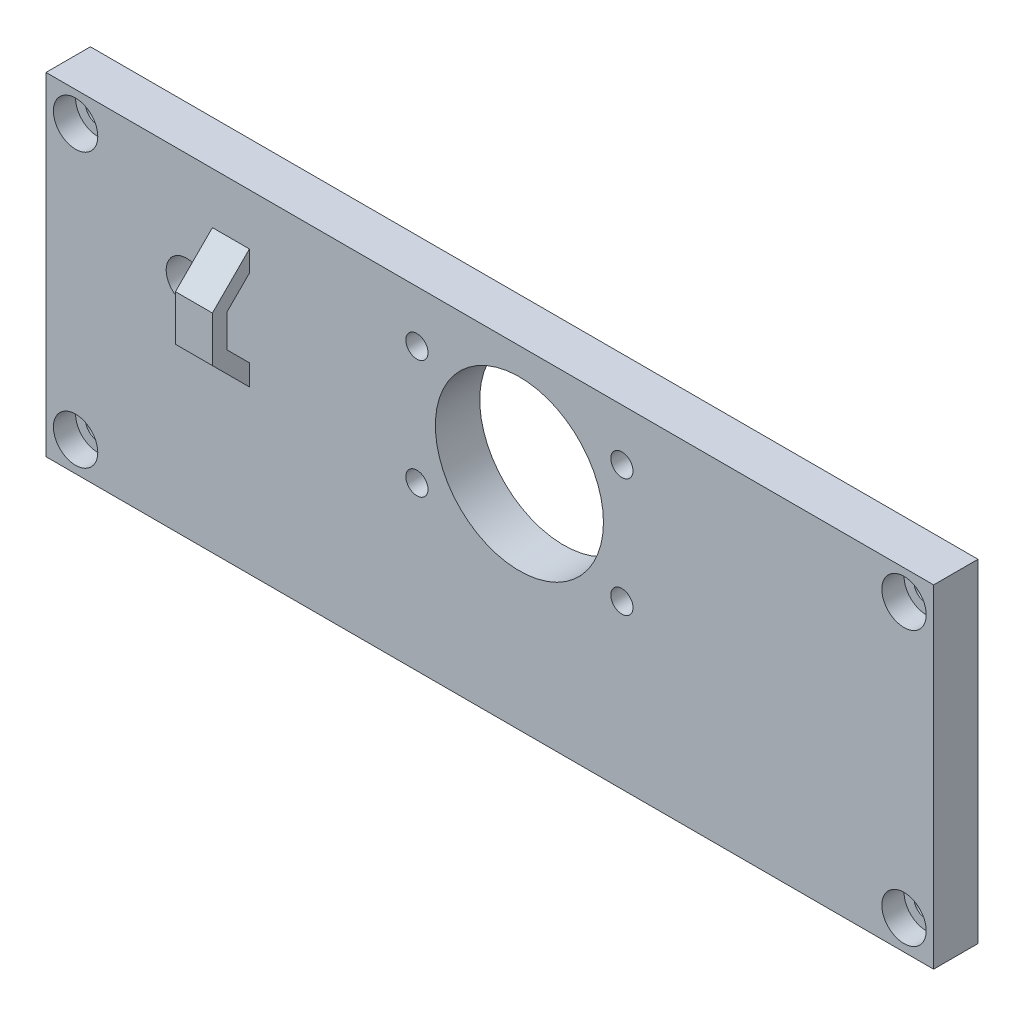
SolidWorks part; units mm, degrees
ref_plane "Front Plane" through (0, 0, 0) normal (0, 0, 1) x (1, 0, 0)
ref_plane "Top Plane" through (0, 0, 0) normal (0, 1, 0) x (1, 0, 0)
ref_plane "Right Plane" through (0, 0, 0) normal (1, 0, 0) x (0, 0, -1)
sketch "Sketch1" plane through (0, 0, 0) normal (0, 0, 1) x (1, 0, 0)
  line L0 (60, 45) -> (60, 0) construction
  line L1 (0, 0) -> (120, 0)
  line L2 (0, 0) -> (0, 45)
  line L3 (0, 45) -> (120, 45)
  line L4 (120, 0) -> (120, 45)
  line L5 (0, 22.5) -> (120, 22.5) construction
  line L6 (50.1436, 38) -> (64, 30) construction
  line L7 (64, 30) -> (42.232, 30) construction
  line L8 (64, 30) -> (64, 38.4979) construction
  circle A0 centre (64, 30) radius 11.3625
  circle A1 centre (4, 41) radius 1.65
  circle A2 centre (4, 4) radius 1.65
  circle A3 centre (116, 41) radius 1.65
  circle A4 centre (116, 4) radius 1.65
  circle A5 centre (50.1436, 38) radius 1.5
  circle A6 centre (50.1436, 22) radius 1.5
  circle A9 centre (77.8564, 22) radius 1.5
  circle A10 centre (77.8564, 38) radius 1.5
  dimension "D3" = 22.725
  dimension "D4" = 4
  dimension "D5" = 3.3
  dimension "D6" = 4
  dimension "D7" = 15
  dimension "D10" = 3
  dimension "D1" = 45
  dimension "D2" = 120
  dimension "D8" = 16
  dimension "D9" = 60
  dimension "D11" = 4
extrude "Boss-Extrude1" add sketch "Sketch1" along normal blind 6
sketch "Sketch2" plane through (0, 0, 6) normal (0, 0, 1) x (1, 0, 0)
  circle A0 centre (116, 4) radius 1.65 construction
  circle A1 centre (116, 41) radius 1.65 construction
  circle A2 centre (4, 4) radius 1.65 construction
  circle A3 centre (4, 41) radius 1.65 construction
  circle A4 centre (116, 4) radius 1.65
  circle A5 centre (116, 41) radius 1.65
  circle A6 centre (4, 4) radius 1.65
  circle A7 centre (4, 41) radius 1.65
  circle A8 centre (4, 41) radius 3
  circle A9 centre (4, 4) radius 3
  circle A10 centre (116, 4) radius 3
  circle A11 centre (116, 41) radius 3
  dimension "D1" = 1.35
extrude "Cut-Extrude1" cut sketch "Sketch2" against normal blind 3
sketch "Sketch3" plane through (0, 0, 6) normal (0, 0, 1) x (1, 0, 0)
  circle A0 centre (19, 30) radius 2.75
  circle A1 centre (64, 30) radius 11.3625 construction
  dimension "D1" = 5.5
  dimension "D2" = 0
  dimension "D3" = 45
extrude "Cut-Extrude2" cut sketch "Sketch3" against normal through all
sketch "Sketch4" plane through (0, 0, 0) normal (-1, 0, 0) x (0, 0, 1)
  line L0 (6, 35.25) -> (9, 32.25)
  line L1 (6, 45) -> (6, 0) construction
  line L2 (9, 32.25) -> (9, 27.75)
  line L3 (9, 27.75) -> (6, 24.75)
  line L4 (6, 45) -> (0, 45) construction
  line L5 (7.4142, 36.6642) -> (11, 33.0784)
  line L6 (11, 33.0784) -> (11, 26.9216)
  line L7 (11, 26.9216) -> (7.4142, 23.3358)
  line L8 (6, 24.75) -> (6, 21.9216)
  line L9 (7.4142, 36.6642) -> (6, 38.0784)
  line L10 (6, 38.0784) -> (6, 35.25)
  line L11 (7.4142, 23.3358) -> (6, 21.9216)
  point P7 (9, 30)
  dimension "D1" = 15
  dimension "D2" = 3
  dimension "D3" = 4.5
  dimension "D4" = 45
  dimension "D5" = 2
extrude "Boss-Extrude2" add sketch "Sketch4" against normal blind 5 from offset 22.5 offset against normal yes
ref_plane "Plane1" through (112, 0, 0) normal (0, -1, 0) x (-1, 0, 0)
